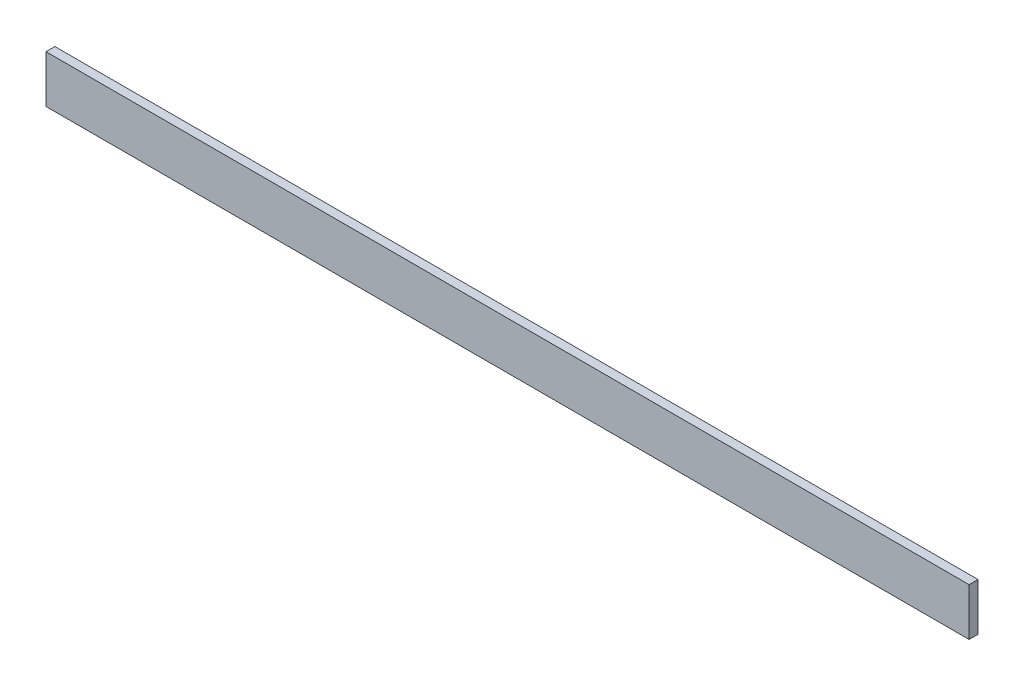
SolidWorks part; units mm, degrees
ref_plane "Alzado" through (0, 0, 0) normal (0, 0, 1) x (1, 0, 0)
ref_plane "Planta" through (0, 0, 0) normal (0, 1, 0) x (1, 0, 0)
ref_plane "Vista lateral" through (0, 0, 0) normal (1, 0, 0) x (0, 0, -1)
sketch "Croquis1" plane through (0, 0, 0) normal (0, 0, 1) x (1, 0, 0)
  line L1 (0, 0) -> (987.6, 0)
  line L2 (0, 0) -> (0, 50.8)
  line L3 (0, 50.8) -> (987.6, 50.8)
  line L4 (987.6, 0) -> (987.6, 50.8)
  dimension "D1" = 50.8
  dimension "D2" = 987.6
extrude "Saliente-Extruir1" add sketch "Croquis1" along normal blind 9.525
